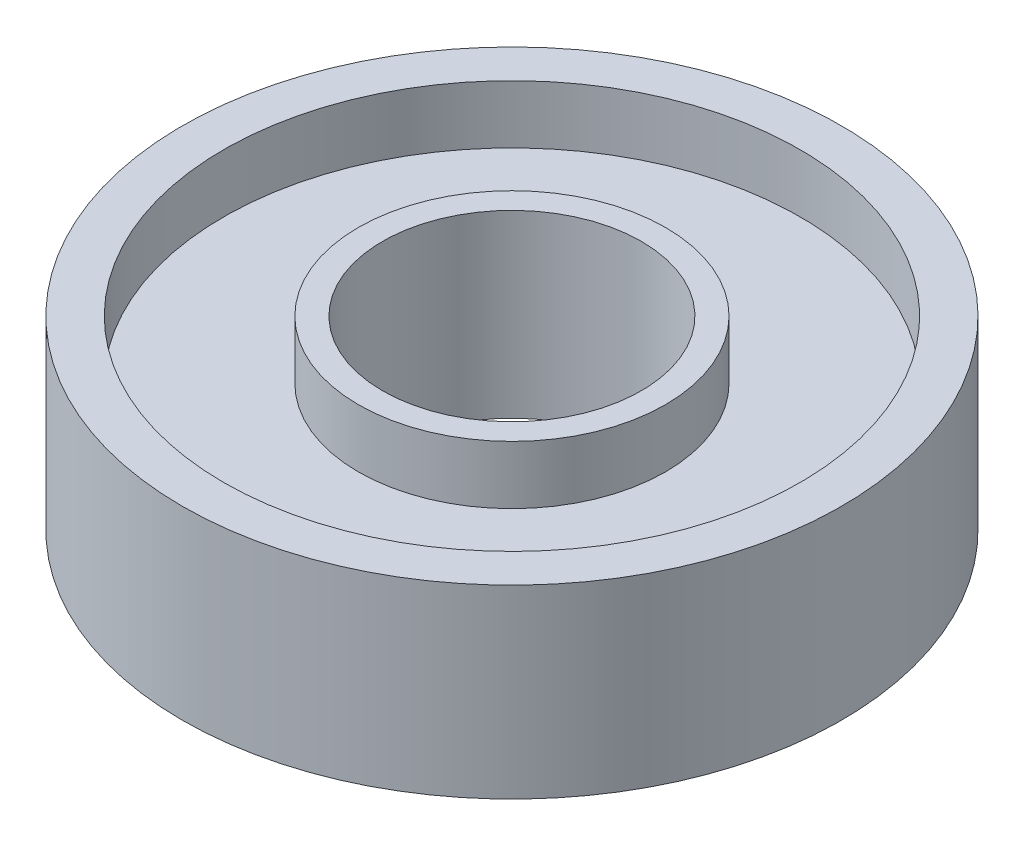
SolidWorks part; units mm, degrees
ref_plane "Front Plane" through (0, 0, 0) normal (0, 0, 1) x (1, 0, 0)
ref_plane "Top Plane" through (0, 0, 0) normal (0, 1, 0) x (1, 0, 0)
ref_plane "Right Plane" through (0, 0, 0) normal (1, 0, 0) x (0, 0, -1)
sketch "Sketch1" plane through (0, 0, 0) normal (0, 1, 0) x (1, 0, 0)
  circle A0 centre (0, 0) radius 12.45
  dimension "D1" = 24.9
extrude "Boss-Extrude1" add sketch "Sketch1" along normal blind 7
sketch "Sketch2" plane through (0, 7, 0) normal (0, 1, 0) x (1, 0, 0)
  circle A0 centre (0, 0) radius 4.89
  dimension "D1" = 9.78
extrude "Cut-Extrude1" cut sketch "Sketch2" against normal through all
sketch "Sketch3" plane through (0, 7, 0) normal (0, 1, 0) x (1, 0, 0)
  circle A0 centre (0, 0) radius 5.8
  circle A2 centre (0, 0) radius 10.89
  dimension "D1" = 11.6
  dimension "D2" = 21.78
extrude "Cut-Extrude2" cut sketch "Sketch3" against normal blind 2.2
sketch "Sketch4" plane through (0, 0, 0) normal (0, -1, 0) x (1, 0, 0)
  circle A0 centre (0, 0) radius 11.15
  circle A1 centre (0, 0) radius 12.45 construction
  dimension "D1" = 1.3
extrude "Cut-Extrude3" cut sketch "Sketch4" against normal blind 0.2
